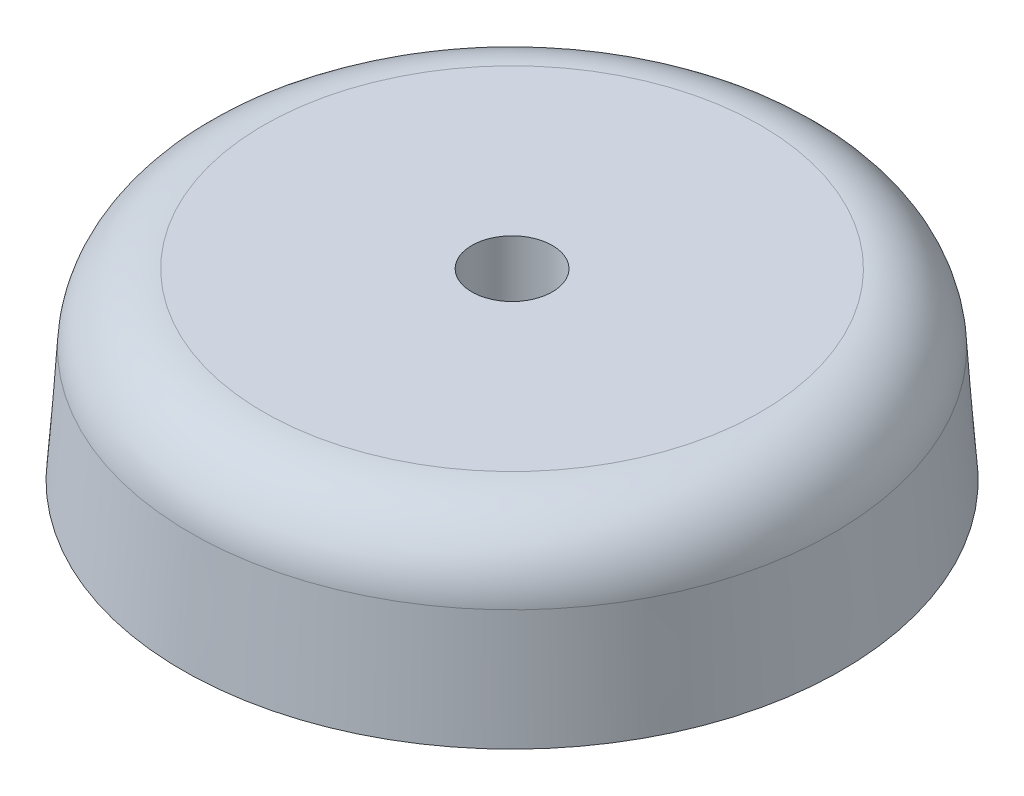
SolidWorks part; units mm, degrees
ref_plane "Front Plane" through (0, 0, 0) normal (0, 0, 1) x (1, 0, 0)
ref_plane "Top Plane" through (0, 0, 0) normal (0, 1, 0) x (1, 0, 0)
ref_plane "Right Plane" through (0, 0, 0) normal (1, 0, 0) x (0, 0, -1)
sketch "Sketch1" plane through (0, 0, 0) normal (0, 0, 1) x (1, 0, 0)
  line L0 (0, 0) -> (0, 5) construction
  line L1 (0, 5) -> (6.7853, 5)
  line L2 (6.8, 0) -> (6.6042, 2.8)
  line L3 (6.6042, 2.8) -> (1.1, 2.8)
  line L4 (1.1, 2.8) -> (1.1, 5)
  line L5 (8.7805, 3.1395) -> (9, 0)
  line L6 (9, 0) -> (6.8, 0)
  arc A0 (6.7853, 5) -> (8.7805, 3.1395) centre (6.7853, 3) cw
  dimension "D6" = 2
  dimension "D1" = 5
  dimension "D2" = 2.8
  dimension "D3" = 2.2
  dimension "D4" = 94
  dimension "D5" = 18
revolve "Revolve1" add sketch "Sketch1" angle 360 about L0
